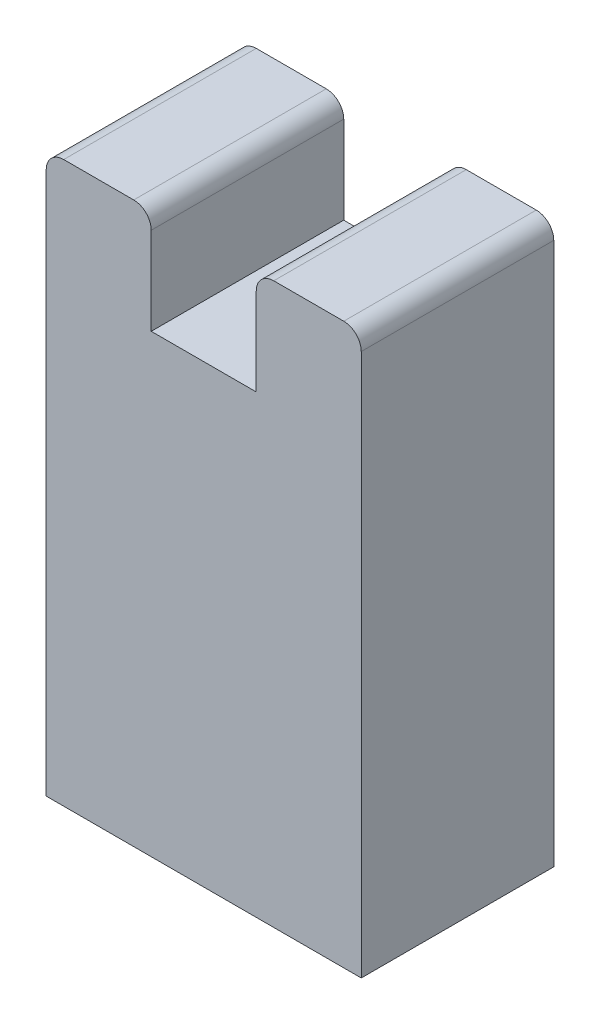
SolidWorks part; units mm, degrees
material "ﾁｰｸ材"
ref_plane "正面" through (0, 0, 0) normal (0, 0, 1) x (1, 0, 0)
ref_plane "平面" through (0, 0, 0) normal (0, 1, 0) x (1, 0, 0)
ref_plane "右側面" through (0, 0, 0) normal (1, 0, 0) x (0, 0, -1)
sketch "ｽｹｯﾁ1" plane through (0, 0, 0) normal (0, 0, 1) x (1, 0, 0)
  line L1 (0, 0) -> (9, 0)
  line L2 (0, 0) -> (0, 16)
  line L3 (0, 16) -> (9, 16)
  line L4 (9, 0) -> (9, 16)
  dimension "D1" = 16
  dimension "D2" = 9
extrude "ﾎﾞｽ - 押し出し1" add sketch "ｽｹｯﾁ1" along normal blind 5.5
sketch "ｽｹｯﾁ2" plane through (0, 0, 5.5) normal (0, 0, 1) x (1, 0, 0)
  line L0 (9, 16) -> (0, 16) construction
  line L1 (3, 16) -> (6, 16)
  line L2 (3, 16) -> (3, 13)
  line L3 (3, 13) -> (6, 13)
  line L4 (6, 16) -> (6, 13)
  line L5 (0, 16) -> (0, 0) construction
  dimension "D1" = 3
  dimension "D2" = 3
  dimension "D3" = 3
extrude "ｶｯﾄ - 押し出し1" cut sketch "ｽｹｯﾁ2" against normal through all
fillet "ﾌｨﾚｯﾄ1" radius 0.5 4 edges at (9, 16, 2.75) (6, 16, 2.75) (3, 16, 2.75) (0, 16, 2.75)
